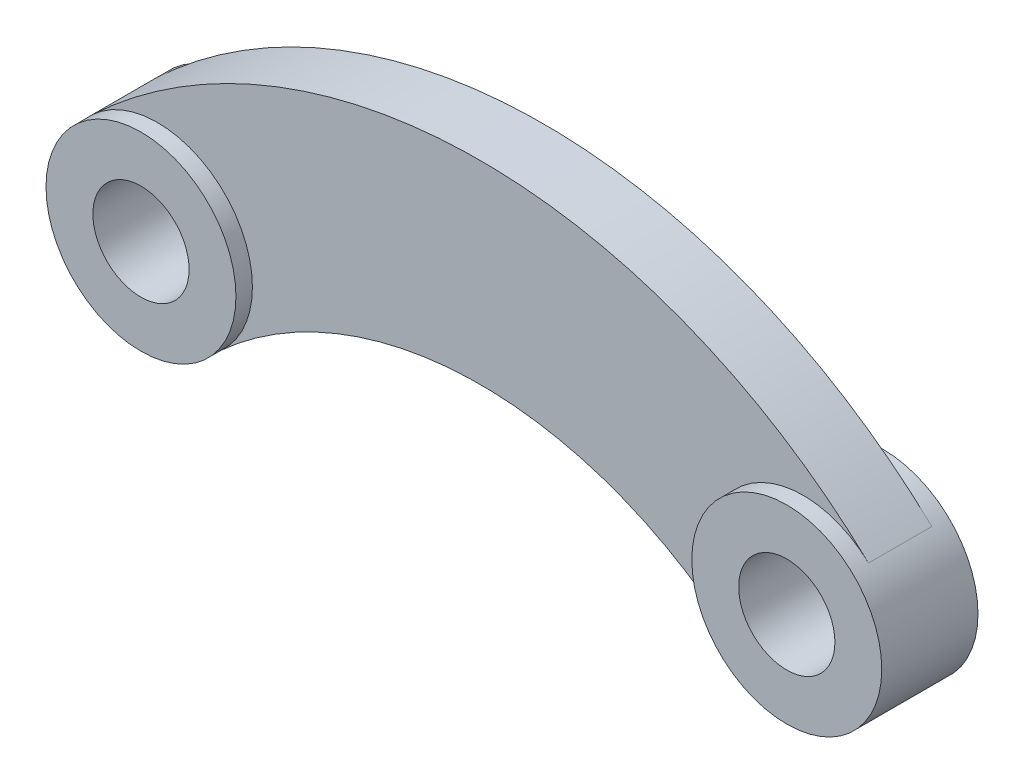
SolidWorks part; units mm, degrees
ref_plane "Front Plane" through (0, 0, 0) normal (0, 0, 1) x (1, 0, 0)
ref_plane "Top Plane" through (0, 0, 0) normal (0, 1, 0) x (1, 0, 0)
ref_plane "Right Plane" through (0, 0, 0) normal (1, 0, 0) x (0, 0, -1)
sketch "Sketch1" plane through (0, 0, 0) normal (0, 0, 1) x (1, 0, 0)
  circle A0 centre (0, 0) radius 38
  arc A1 (-51.5499, 54.4758) -> (50.3289, -55.6057) centre (0, 0) ccw
  circle A2 centre (510, 0) radius 38
  arc A3 (459.6711, -55.6057) -> (561.5499, 54.4758) centre (510, 0) ccw
  arc A4 (50.3289, -55.6057) -> (459.6711, -55.6057) centre (255, -281.7357) cw
  arc A5 (-51.5499, 54.4758) -> (561.5499, 54.4758) centre (255, -269.4736) cw
  point P3 (0, 0)
  point P6 (0, 0)
  point P10 (0, 0)
  dimension "D1" = 76
  dimension "D2" = 75
  dimension "D3" = 446
  dimension "D5" = 305
  dimension "D4" = 510
extrude "Boss-Extrude1" add sketch "Sketch1" along normal mid plane 50
sketch "Sketch2" plane through (0, 0, 0) normal (0, 0, 1) x (1, 0, 0)
  circle A1 centre (0, 0) radius 75
  circle A3 centre (510, 0) radius 75
  circle A4 centre (510, 0) radius 38 construction
  circle A5 centre (0, 0) radius 38 construction
  circle A6 centre (510, 0) radius 38
  circle A7 centre (0, 0) radius 38
  dimension "D1" = 150
extrude "Boss-Extrude2" add sketch "Sketch2" along normal mid plane 76
